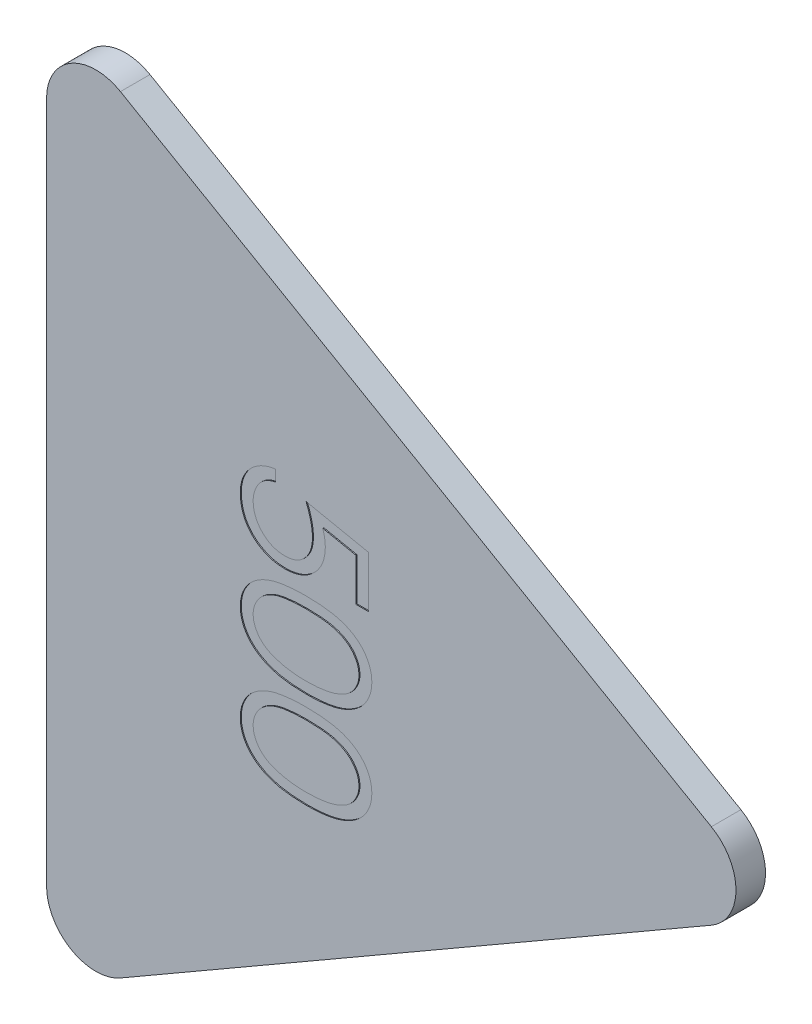
SolidWorks part; units mm, degrees
ref_plane "Front Plane" through (0, 0, 0) normal (1, 0, 0) x (0, 1, 0)
ref_plane "Top Plane" through (0, 0, 0) normal (0, 0, 1) x (0, 1, 0)
ref_plane "Right Plane" through (0, 0, 0) normal (0, 1, 0) x (-1, 0, 0)
sketch "Sketch1" plane through (0, 0, 0) normal (0, 0, 1) x (0, 1, 0)
  line L0 (0, 0) -> (57.3152, 0) construction
  line L1 (4.3301, -42.5) -> (38.9711, 17.5)
  line L2 (34.641, 25) -> (-34.641, 25)
  line L3 (-38.9711, 17.5) -> (-4.3301, -42.5)
  circle A0 centre (0, 0) radius 25 construction
  arc A1 (-4.3301, -42.5) -> (4.3301, -42.5) centre (0, -40) ccw
  arc A2 (38.9711, 17.5) -> (34.641, 25) centre (34.641, 20) ccw
  arc A3 (-38.9711, 17.5) -> (-34.641, 25) centre (-34.641, 20) cw
  dimension "D1" = 50
  dimension "D2" = 5
extrude "Boss-Extrude1" add sketch "Sketch1" along normal blind 3
sketch "Sketch2" plane through (0, 0, 3) normal (0, 0, 1) x (0, -1, 0)
  point P0 (0, 0)
sketch "Sketch3" plane through (0, 0, 3) normal (0, 0, 1) x (0, -1, 0)
  text T0 "500" font "Century Gothic" height in points 48
extrude "Cut-Extrude1" cut sketch "Sketch3" against normal blind 0.1
